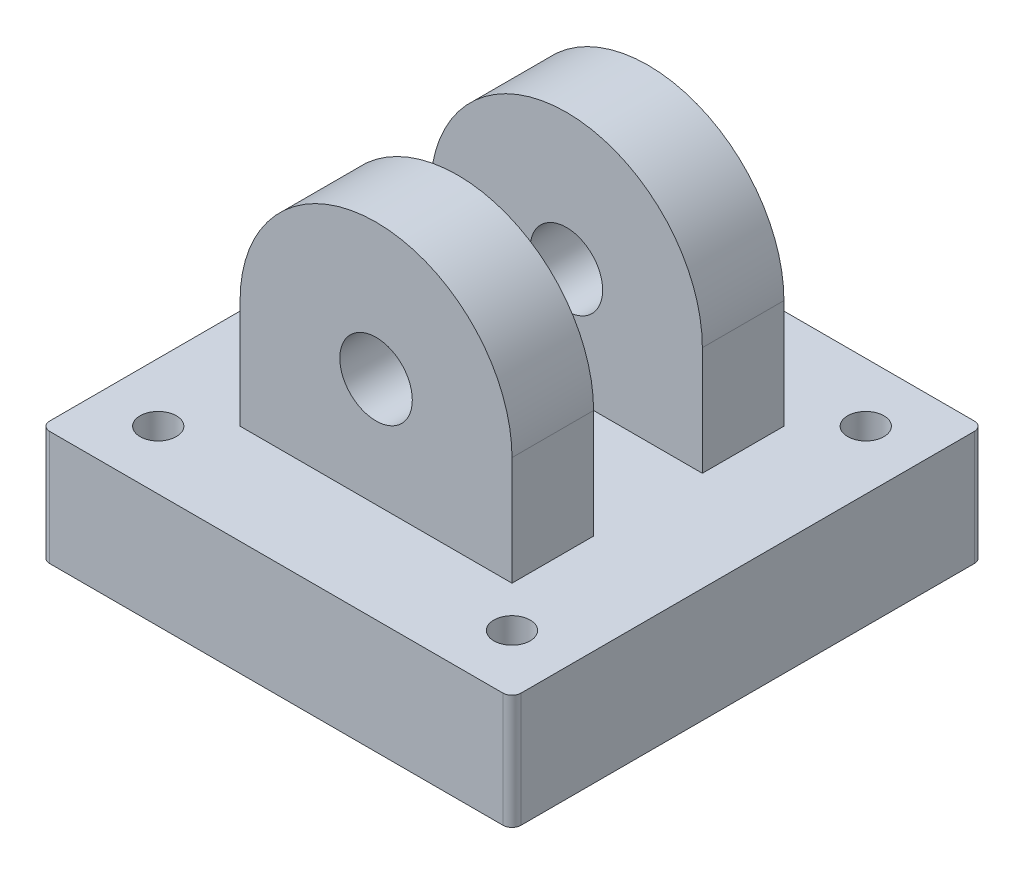
SolidWorks part; units mm, degrees
ref_plane "Front Plane" through (0, 0, 0) normal (0, 0, 1) x (1, 0, 0)
ref_plane "Top Plane" through (0, 0, 0) normal (0, 1, 0) x (1, 0, 0)
ref_plane "Right Plane" through (0, 0, 0) normal (1, 0, 0) x (0, 0, -1)
sketch "Sketch1" plane through (0, 0, 0) normal (0, 1, 0) x (1, 0, 0)
  line L1 (82.55, -82.55) -> (-82.55, -82.55)
  line L2 (82.55, -82.55) -> (82.55, 82.55)
  line L3 (82.55, 82.55) -> (-82.55, 82.55)
  line L4 (-82.55, -82.55) -> (-82.55, 82.55)
  line L5 (82.55, -82.55) -> (-82.55, 82.55) construction
  line L6 (82.55, 82.55) -> (-82.55, -82.55) construction
  point P0 (0, 0)
  dimension "D1" = 165.1
extrude "Boss-Extrude1" add sketch "Sketch1" along normal blind 38.1 and the other way blind 2
sketch "Sketch3" plane through (0, 38.1, 0) normal (0, 1, 0) x (1, 0, 0)
  line L1 (47.625, -47.625) -> (-47.625, -47.625)
  line L2 (47.625, -47.625) -> (47.625, 47.625)
  line L3 (47.625, 47.625) -> (-47.625, 47.625)
  line L4 (-47.625, -47.625) -> (-47.625, 47.625)
  line L5 (47.625, -47.625) -> (-47.625, 47.625) construction
  line L6 (47.625, 47.625) -> (-47.625, -47.625) construction
  point P0 (0, 0)
  dimension "D1" = 95.25
extrude "Boss-Extrude2" add sketch "Sketch3" along normal blind 38.1
sketch "Sketch4" plane through (0, 0, 47.625) normal (0, 0, 1) x (1, 0, 0)
  line L0 (-47.625, 76.2) -> (47.625, 76.2)
  arc A0 (47.625, 76.2) -> (-47.625, 76.2) centre (0, 76.2) ccw
  dimension "D1" = 47.625
extrude "Boss-Extrude3" add sketch "Sketch4" against normal up to vertex (95.25 mm away) up to point (47.625, 76.2, -47.625)
sketch "Sketch5" plane through (0, 0, 47.625) normal (0, 0, 1) x (1, 0, 0)
  circle A0 centre (0, 76.2) radius 12.7
  dimension "D1" = 25.4
extrude "Cut-Extrude1" cut sketch "Sketch5" against normal through all
sketch "Sketch6" plane through (-47.625, 0, 0) normal (-1, 0, 0) x (0, 0, 1)
  line L0 (-82.55, 38.1) -> (82.55, 38.1) construction
  line L1 (-19.05, 38.1) -> (19.05, 38.1)
  line L2 (-19.05, 38.1) -> (-19.05, 123.825)
  line L3 (-19.05, 123.825) -> (19.05, 123.825)
  line L4 (19.05, 38.1) -> (19.05, 123.825)
  line L5 (47.625, 123.825) -> (-47.625, 123.825) construction
  line L6 (-47.625, 123.825) -> (-47.625, 76.2) construction
  dimension "D1" = 38.1
  dimension "D2" = 28.575
extrude "Cut-Extrude2" cut sketch "Sketch6" against normal through all
fillet "Fillet1" radius 3.175 4 edges at (82.55, 18.05, 82.55) (-82.55, 18.05, -82.55) (82.55, 18.05, -82.55) (-82.55, 18.05, 82.55)
sketch "Sketch7" plane through (0, -2, 0) normal (0, -1, 0) x (1, 0, 0)
  circle A0 centre (0, 0) radius 26
  dimension "D1" = 52
extrude "Cut-Extrude3" cut sketch "Sketch7" against normal blind 36.83
sketch "Sketch8" plane through (0, -2, 0) normal (0, -1, 0) x (1, 0, 0)
  circle A0 centre (0, 0) radius 76.2
  circle A1 centre (0, 0) radius 69.85
  dimension "D1" = 152.4
  dimension "D2" = 139.7
extrude "Cut-Extrude4" cut sketch "Sketch8" against normal blind 8
sketch "Sketch13" plane through (-82.55, 0, 0) normal (-1, 0, 0) x (0, 0, 1)
  line L0 (-79.375, 18.05) -> (79.375, 18.05) construction
  line L1 (-79.375, 38.1) -> (-79.375, -2) construction
  line L2 (79.375, -2) -> (79.375, 38.1) construction
hole_wizard "1/2-14 NPSM Tapped Hole2" positions "Sketch14" profile "Sketch15" tap size "1/2-14 NPSM" standard "ANSI Inch"
sketch "Sketch14" plane through (-82.55, 0, 0) normal (-1, 0, 0) x (0, 0, 1)
  line L0 (-79.375, 18.05) -> (79.375, 18.05) construction
  point P0 (0, 18.05)
sketch "Sketch15" plane through (-82.55, 18.05, 0) normal (0, 1, 0) x (0, 0, 1)
  line L0 (0, 0) -> (0, 69.2003)
  line L1 (0, 69.2003) -> (9.4869, 63.5)
  line L2 (9.4869, 63.5) -> (9.4869, 1.6002)
  line L3 (9.4869, 1.6002) -> (11.0871, 0)
  line L5 (11.0871, 0) -> (0, 0)
  line L6 (-9.4869, 1.6002) -> (-11.0871, 0) construction
  line L10 (0, 69.2003) -> (-9.4869, 63.5) construction
  line L11 (0, -6.35) -> (0, 107.95) construction
  dimension "Tap Drill Dia." = 18.9738
  dimension "Tap Drill Depth" = 63.5
  dimension "Near C'Sink Dia." = 22.1742
  dimension "Near C'Sink Angle" = 90
  dimension "Drill Angle" = 118
cosmetic thread "Hole Thread2" parameters "D1"=41.91, "D2"=20.9042
sketch "Sketch16" plane through (0, -2, 0) normal (0, -1, 0) x (1, 0, 0)
  line L0 (-82.55, -79.375) -> (-82.55, 79.375) construction
  circle A0 centre (-50.55, 0) radius 6.35
  dimension "D1" = 12.7
  dimension "D2" = 32
extrude "Cut-Extrude5" cut sketch "Sketch16" against normal blind 25
sketch "Sketch17" plane through (0, -2, 0) normal (0, -1, 0) x (1, 0, 0)
  line L1 (61.9638, -61.9638) -> (-61.9638, -61.9638) construction
  line L2 (61.9638, -61.9638) -> (61.9638, 61.9638) construction
  line L3 (61.9638, 61.9638) -> (-61.9638, 61.9638) construction
  line L4 (-61.9638, -61.9638) -> (-61.9638, 61.9638) construction
  line L5 (61.9638, -61.9638) -> (-61.9638, 61.9638) construction
  line L6 (61.9638, 61.9638) -> (-61.9638, -61.9638) construction
  circle A0 centre (0, 0) radius 87.63 construction
  circle A1 centre (-61.9638, 61.9638) radius 6.35
  circle A2 centre (61.9638, 61.9638) radius 6.35
  circle A3 centre (61.9638, -61.9638) radius 6.35
  circle A4 centre (-61.9638, -61.9638) radius 6.35
  dimension "D1" = 175.26
  dimension "D2" = 12.7
extrude "Cut-Extrude6" cut sketch "Sketch17" against normal through all
